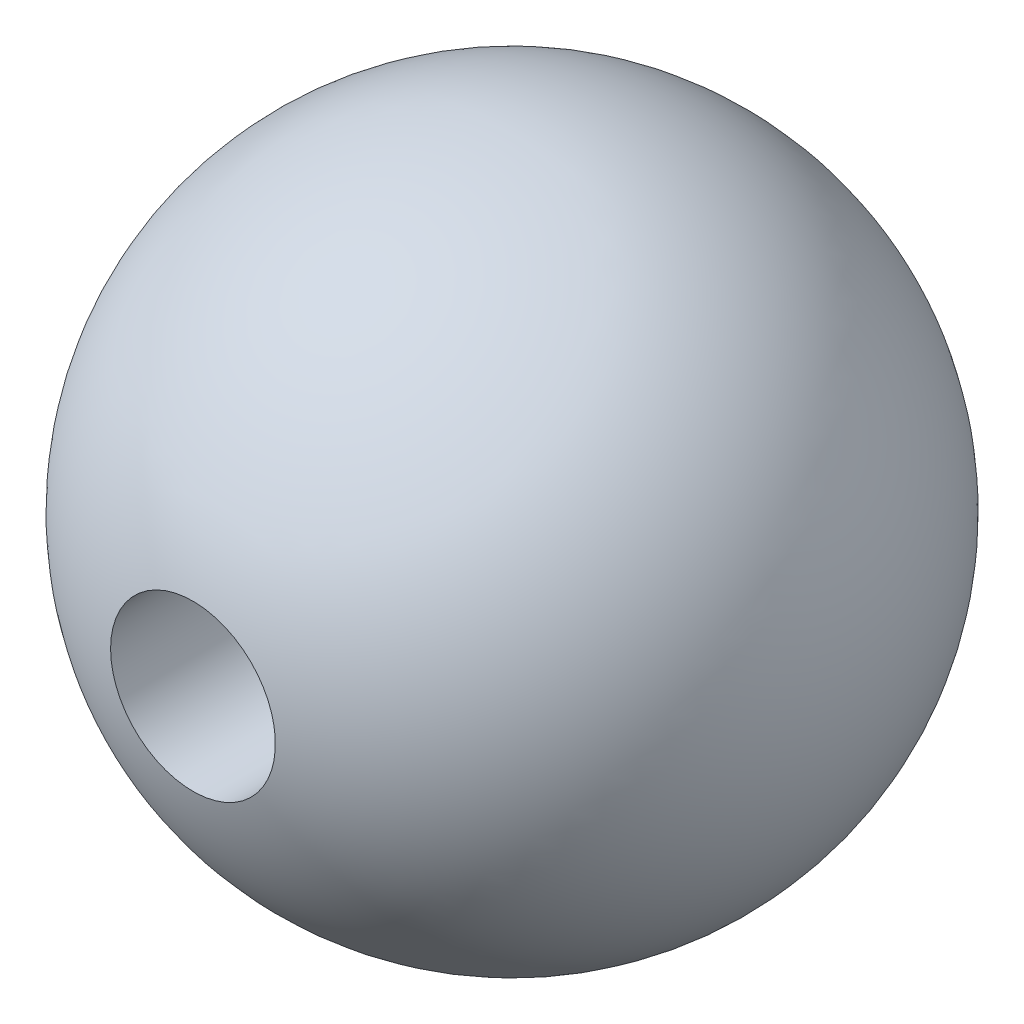
SolidWorks part; units mm, degrees
material "Custom Plastic"
ref_plane "Front Plane" through (0, 0, 0) normal (0, 0, 1) x (1, 0, 0)
ref_plane "Top Plane" through (0, 0, 0) normal (0, 1, 0) x (1, 0, 0)
ref_plane "Right Plane" through (0, 0, 0) normal (1, 0, 0) x (0, 0, -1)
sketch "Sketch1" plane through (0, 0, 0) normal (0, 0, 1) x (1, 0, 0)
  line L0 (0, -6.35) -> (0, 6.35) construction
  line L1 (0, -6.35) -> (0, 6.35)
  arc A0 (0, -6.35) -> (0, 6.35) centre (0, 0) ccw
  point P3 (0, 0)
  dimension "D1" = 12.7
revolve "Revolve1" add sketch "Sketch1" angle 360 about L0
sketch "Sketch2" plane through (0, 0, 0) normal (0, 0, 1) x (1, 0, 0)
  circle A0 centre (0, 0) radius 1.5875
  dimension "D1" = 3.175
extrude "Cut-Extrude1" cut sketch "Sketch2" against normal mid plane 25.4
